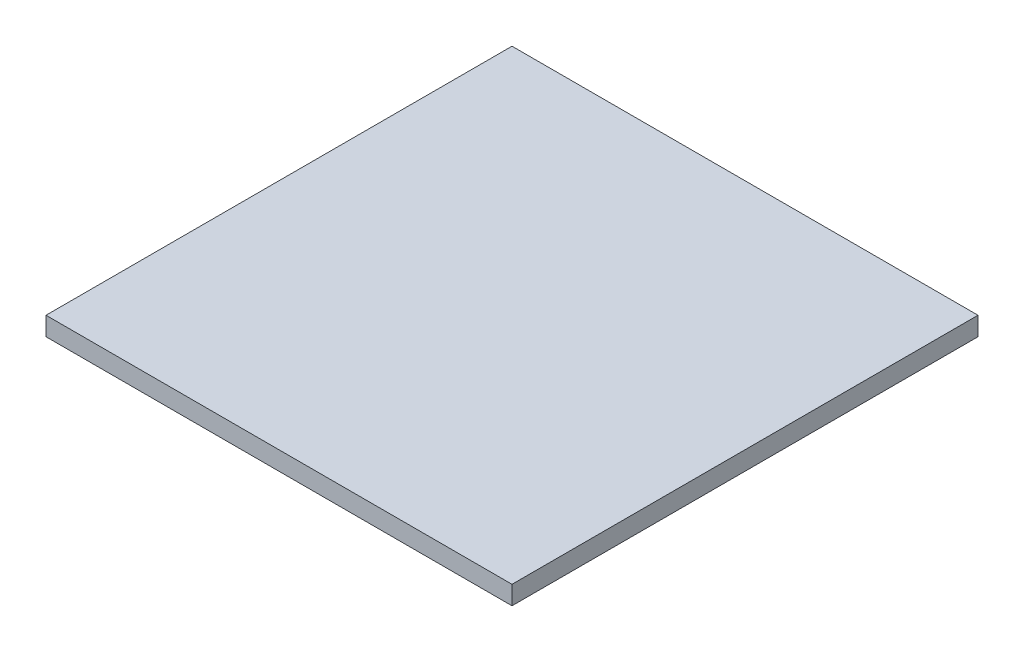
SolidWorks part; units mm, degrees
ref_plane "Front Plane" through (0, 0, 0) normal (0, 0, 1) x (1, 0, 0)
ref_plane "Top Plane" through (0, 0, 0) normal (0, 1, 0) x (1, 0, 0)
ref_plane "Right Plane" through (0, 0, 0) normal (1, 0, 0) x (0, 0, -1)
sketch "Sketch6" plane through (0, 0, 0) normal (0, 1, 0) x (1, 0, 0)
  line L1 (0, 0) -> (50, 0)
  line L2 (0, 0) -> (0, 50)
  line L3 (0, 50) -> (50, 50)
  line L4 (50, 0) -> (50, 50)
  dimension "D1" = 50
  dimension "D2" = 50
extrude "Boss-Extrude1" add sketch "Sketch6" along normal blind 2
